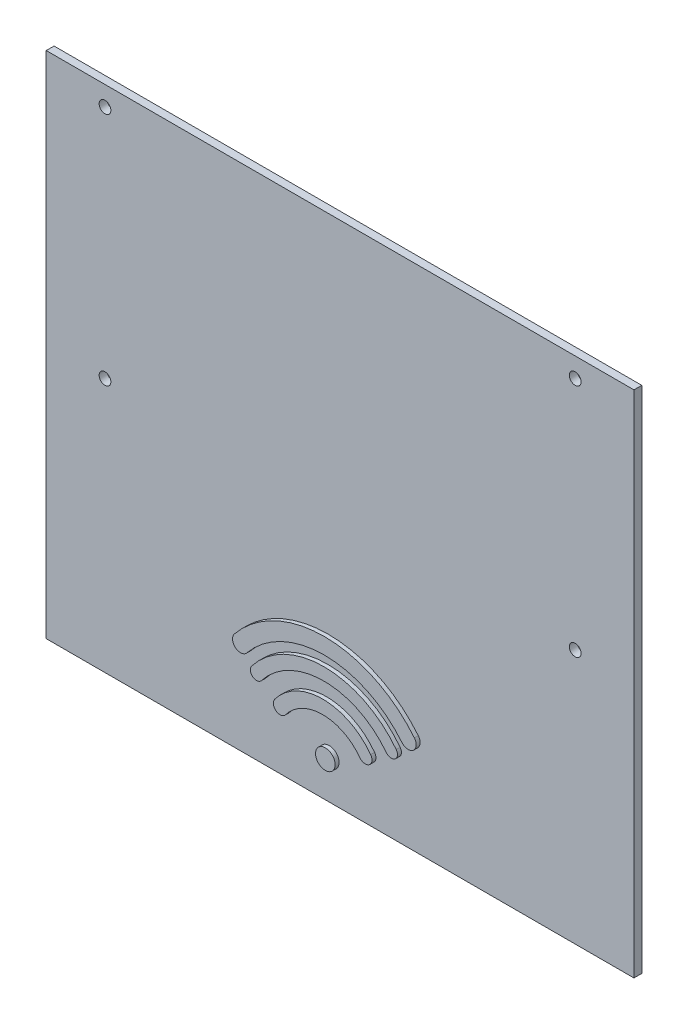
SolidWorks part; units mm, degrees
ref_plane "Front Plane" through (0, 0, 0) normal (0, 0, 1) x (1, 0, 0)
ref_plane "Top Plane" through (0, 0, 0) normal (0, 1, 0) x (1, 0, 0)
ref_plane "Right Plane" through (0, 0, 0) normal (1, 0, 0) x (0, 0, -1)
sketch "Sketch1" plane through (0, 0, 0) normal (0, 0, 1) x (1, 0, 0)
  line L1 (-76.8867, 40.9897) -> (73.1133, 40.9897)
  line L2 (-76.8867, 40.9897) -> (-76.8867, -89.0103)
  line L3 (-76.8867, -89.0103) -> (73.1133, -89.0103)
  line L4 (73.1133, 40.9897) -> (73.1133, -89.0103)
  circle A0 centre (-61.8867, 35.9897) radius 1.5
  circle A1 centre (58.1133, 35.9897) radius 1.5
  circle A2 centre (-61.8867, -24.0103) radius 1.5
  circle A3 centre (58.1133, -24.0103) radius 1.5
  dimension "D3" = 3
  dimension "D4" = 3
  dimension "D5" = 3
  dimension "D6" = 3
  dimension "D1" = 150
  dimension "D2" = 130
  dimension "D7" = 60
  dimension "D8" = 60
  dimension "D9" = 5
  dimension "D10" = 5
  dimension "D11" = 15
  dimension "D12" = 15
  dimension "D13" = 15
  dimension "D14" = 15
extrude "Boss-Extrude1" add sketch "Sketch1" along normal blind 2
sketch "Sketch3" plane through (0, 0, 2) normal (0, 0, 1) x (1, 0, 0)
  line L0 (-76.8867, -89.0103) -> (73.1133, -89.0103) construction
  circle A0 centre (-4.6481, -79.0103) radius 2.5
  arc A1 (-16.1885, -73.2563) -> (5.5414, -73.2563) centre (-5.3236, -81.3027) cw construction
  arc A2 (6.9232, -72.233) -> (-17.5704, -72.233) centre (-5.3236, -81.3027) ccw
  arc A3 (4.1596, -74.2797) -> (-14.8067, -74.2797) centre (-5.3236, -81.3027) ccw
  arc A4 (4.1596, -74.2797) -> (6.9232, -72.233) centre (5.5414, -73.2563) ccw
  arc A5 (-17.5704, -72.233) -> (-14.8067, -74.2797) centre (-16.1885, -73.2563) ccw
  arc A6 (-26.2871, -64.2626) -> (16.4865, -64.2626) centre (-4.9003, -81.6456) cw construction
  arc A7 (18.0784, -62.9687) -> (-27.879, -62.9687) centre (-4.9003, -81.6456) ccw
  arc A8 (14.8946, -65.5565) -> (-24.6953, -65.5565) centre (-4.9003, -81.6456) ccw
  arc A9 (14.8946, -65.5565) -> (18.0784, -62.9687) centre (16.4865, -64.2626) ccw
  arc A10 (-27.879, -62.9687) -> (-24.6953, -65.5565) centre (-26.2871, -64.2626) ccw
  arc A11 (-22.1967, -68.8184) -> (12.1809, -68.8184) centre (-5.0079, -82.005) cw construction
  arc A12 (13.443, -67.8501) -> (-23.4588, -67.8501) centre (-5.0079, -82.005) ccw
  arc A13 (10.9187, -69.7867) -> (-20.9345, -69.7867) centre (-5.0079, -82.005) ccw
  arc A14 (10.9187, -69.7867) -> (13.443, -67.8501) centre (12.1809, -68.8184) ccw
  arc A15 (-23.4588, -67.8501) -> (-20.9345, -69.7867) centre (-22.1967, -68.8184) ccw
  point P7 (-5.3236, -67.7826)
  point P15 (-4.9003, -54.0854)
  point P20 (-5.0079, -60.3407)
  dimension "D1" = 5
  dimension "D2" = 10
extrude "Boss-Extrude2" add sketch "Sketch3" along normal blind 1
